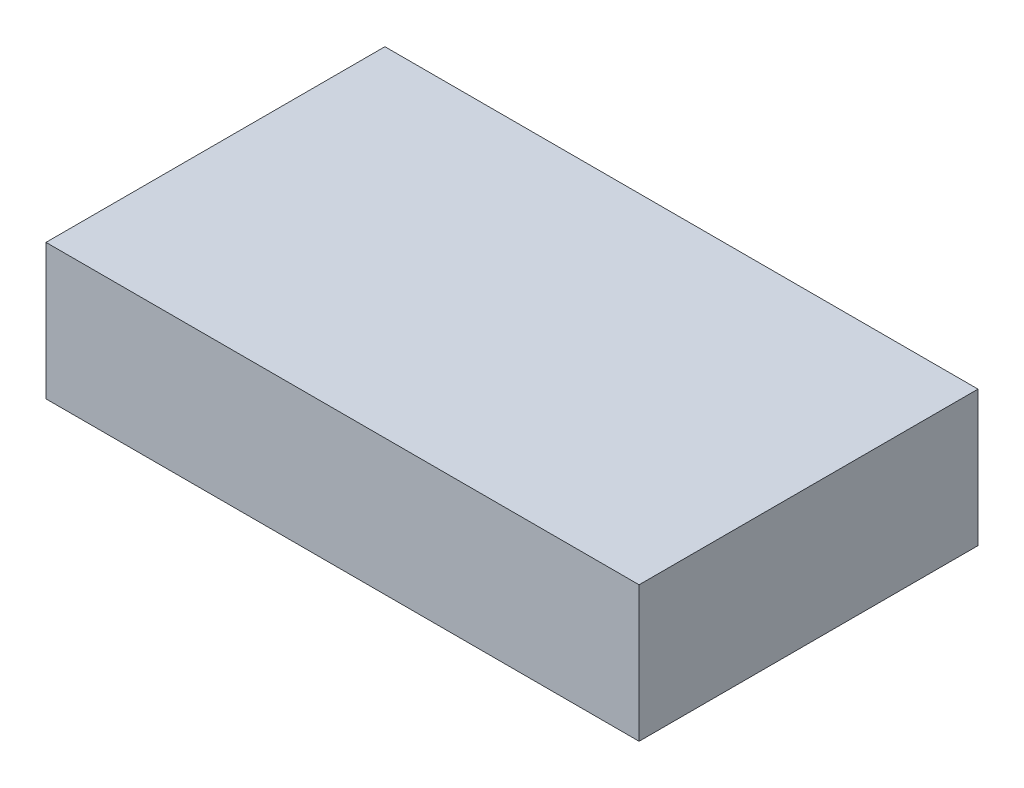
SolidWorks part; units mm, degrees
ref_plane "Front Plane" through (0, 0, 0) normal (0, 0, 1) x (1, 0, 0)
ref_plane "Top Plane" through (0, 0, 0) normal (0, 1, 0) x (1, 0, 0)
ref_plane "Right Plane" through (0, 0, 0) normal (1, 0, 0) x (0, 0, -1)
sketch "Sketch1" plane through (0, 0, 0) normal (0, 1, 0) x (1, 0, 0)
  line L0 (-639.0323, -228.0645) -> (1110.9677, -228.0645)
  line L1 (-639.0323, -228.0645) -> (-639.0323, 771.9355)
  line L2 (-639.0323, 771.9355) -> (1110.9677, 771.9355)
  line L3 (1110.9677, 771.9355) -> (1110.9677, -228.0645)
  dimension "D1" = 1750
  dimension "D2" = 1000
extrude "Boss-Extrude1" add sketch "Sketch1" along normal blind 400
